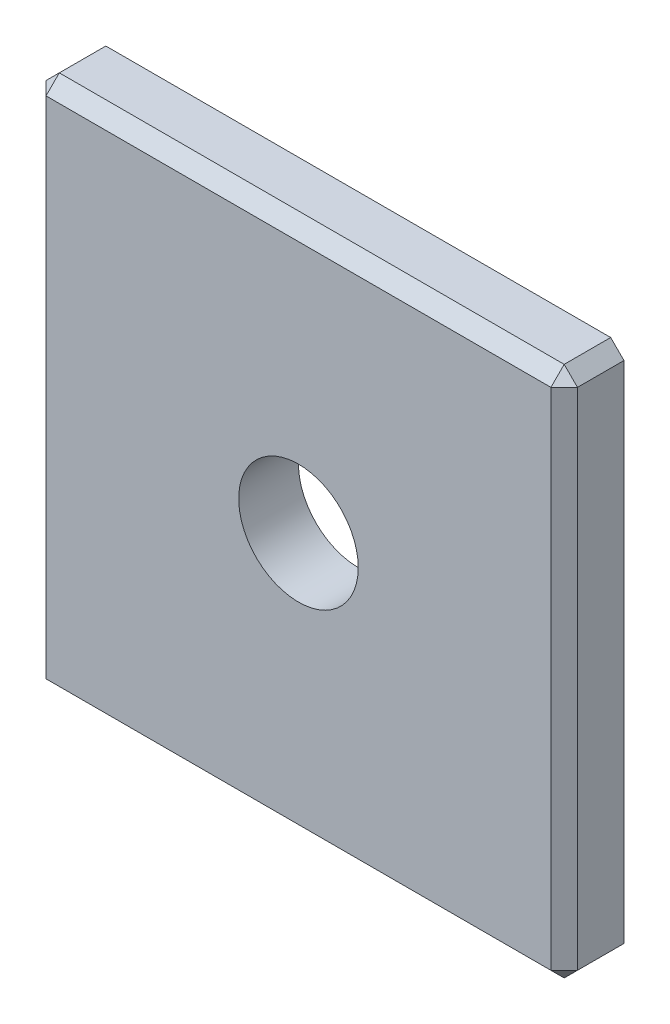
SolidWorks part; units mm, degrees
ref_plane "Alzado" through (0, 0, 0) normal (0, 0, 1) x (1, 0, 0)
ref_plane "Planta" through (0, 0, 0) normal (0, 1, 0) x (1, 0, 0)
ref_plane "Vista lateral" through (0, 0, 0) normal (1, 0, 0) x (0, 0, -1)
sketch "Croquis1" plane through (0, 0, 0) normal (0, 0, 1) x (1, 0, 0)
  line L1 (-20, -20) -> (20, -20)
  line L2 (-20, -20) -> (-20, 20)
  line L3 (-20, 20) -> (20, 20)
  line L4 (20, -20) -> (20, 20)
  line L5 (-20, -20) -> (20, 20) construction
  line L6 (-20, 20) -> (20, -20) construction
  circle A0 centre (0, 0) radius 4.5
  point P0 (0, 0)
  dimension "D3" = 9
  dimension "D1" = 40
  dimension "D2" = 40
extrude "Saliente-Extruir1" add sketch "Croquis1" along normal blind 4.5
chamfer "Chaflán1" distance 1 angle 45 8 edges at (0, -20, 4.5) (20, -20, 2.25) (20, 0, 4.5) (20, 20, 2.25) (0, 20, 4.5) (-20, 20, 2.25) (-20, 0, 4.5) (-20, -20, 2.25)
